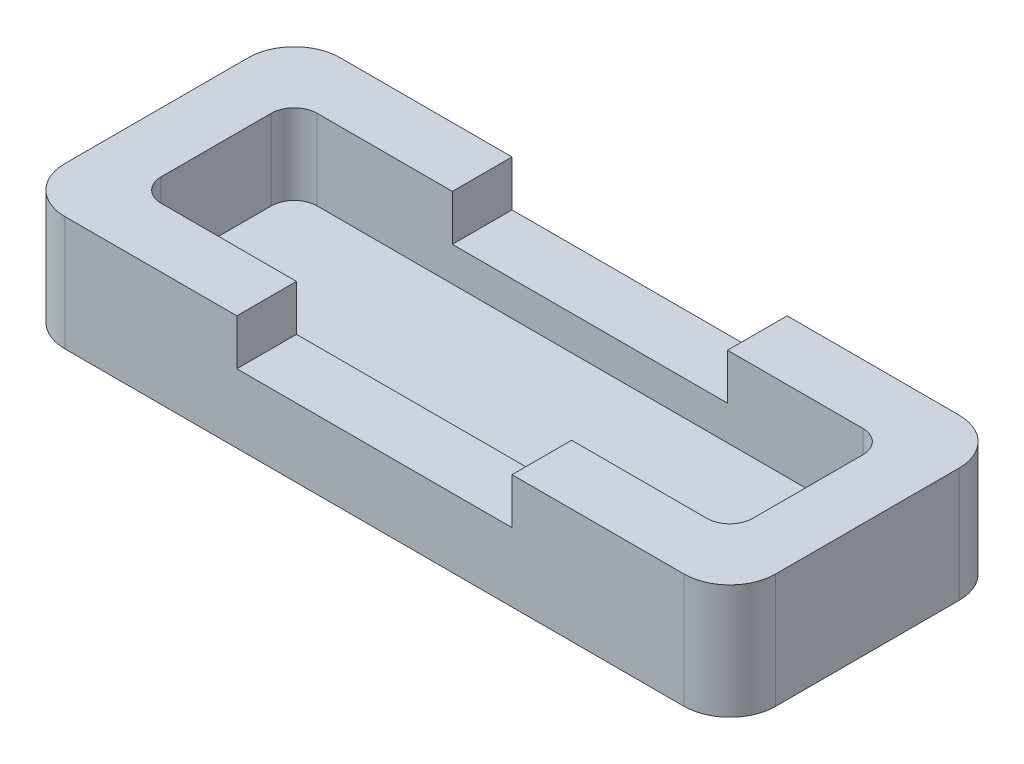
SolidWorks part; units mm, degrees
other "Markup1"
sketch "Sketch3" plane through (15.5, 5, -6) normal (0.0696, 0.7368, -0.6725) x (0.9734, -0.1976, -0.1158)
ref_plane "Front Plane" through (0, 0, 0) normal (0, 0, 1) x (1, 0, 0)
ref_plane "Top Plane" through (0, 0, 0) normal (0, 1, 0) x (1, 0, 0)
ref_plane "Right Plane" through (0, 0, 0) normal (1, 0, 0) x (0, 0, -1)
sketch "Sketch1" plane through (0, 0, 0) normal (0, 1, 0) x (1, 0, 0)
  line L1 (-15.5, 6) -> (15.5, 6)
  line L2 (-15.5, 6) -> (-15.5, -6)
  line L3 (-15.5, -6) -> (15.5, -6)
  line L4 (15.5, 6) -> (15.5, -6)
  line L5 (-15.5, 6) -> (15.5, -6) construction
  line L6 (-15.5, -6) -> (15.5, 6) construction
  point P0 (0, 0)
  dimension "D1" = 31
  dimension "D2" = 12
extrude "Boss-Extrude1" add sketch "Sketch1" along normal blind 5
shell "Shell1" thickness 2.6
sketch "Sketch2" plane through (0, 5, 0) normal (0, 1, 0) x (1, 0, 0)
  line L0 (15.5, 6) -> (-15.5, 6) construction
  line L1 (-6, -6) -> (6, -6)
  line L2 (-6, -6) -> (-6, 6)
  line L3 (-6, 6) -> (6, 6)
  line L4 (6, -6) -> (6, 6)
  line L5 (-6, -6) -> (6, 6) construction
  line L6 (-6, 6) -> (6, -6) construction
  point P0 (0, 0)
  dimension "D1" = 12
extrude "Cut-Extrude1" cut sketch "Sketch2" against normal blind 2
fillet "Fillet1" radius 2 4 edges at (15.5, 2.5, 6) (15.5, 2.5, -6) (-15.5, 2.5, -6) (-15.5, 2.5, 6)
fillet "Fillet2" radius 1 4 edges at (-12.9, 3.25, -3.4) (-12.9, 3.25, 3.4) (12.9, 3.25, 3.4) (12.9, 3.25, -3.4)
